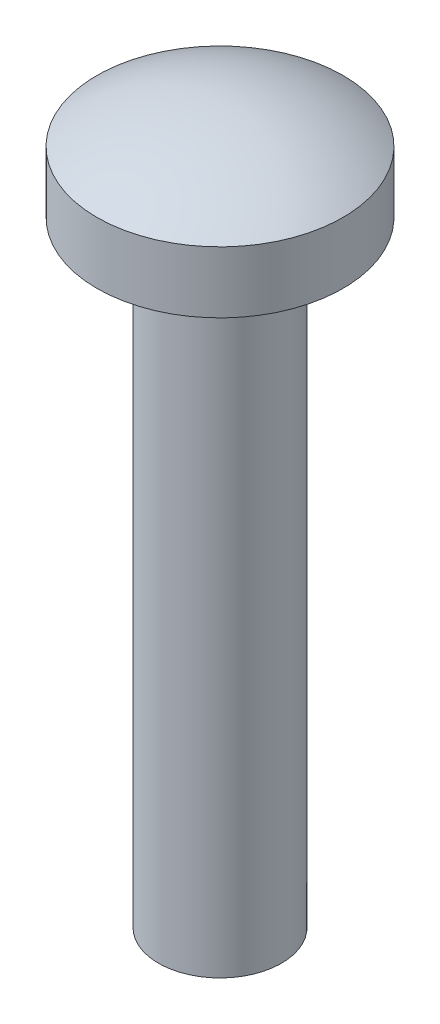
SolidWorks part; units mm, degrees
ref_plane "Front Plane" through (0, 0, 0) normal (0, 0, 1) x (1, 0, 0)
ref_plane "Top Plane" through (0, 0, 0) normal (0, 1, 0) x (1, 0, 0)
ref_plane "Right Plane" through (0, 0, 0) normal (1, 0, 0) x (0, 0, -1)
sketch "Sketch2" plane through (0, 0, 0) normal (1, 0, 0) x (0, 0, -1)
  line L0 (0, 0) -> (2, 0)
  line L1 (55, 0) -> (-55, 0) construction
  line L2 (2, 0) -> (2, 1)
  line L3 (0, 55) -> (0, -55) construction
  line L4 (0, 1.6) -> (0, 0)
  arc A0 (2, 1) -> (0, 1.6) centre (0, -2.0333) ccw
  dimension "D4" = 0
  dimension "D1" = 2
  dimension "D2" = 1.6
  dimension "D3" = 1
revolve "Revolve1" add sketch "Sketch2" angle 360 about L4
sketch "Sketch3" plane through (0, 0, 0) normal (0, -1, 0) x (1, 0, 0)
  circle A0 centre (0, 0) radius 1
  dimension "D1" = 2
extrude "Boss-Extrude1" add sketch "Sketch3" along normal blind 10
